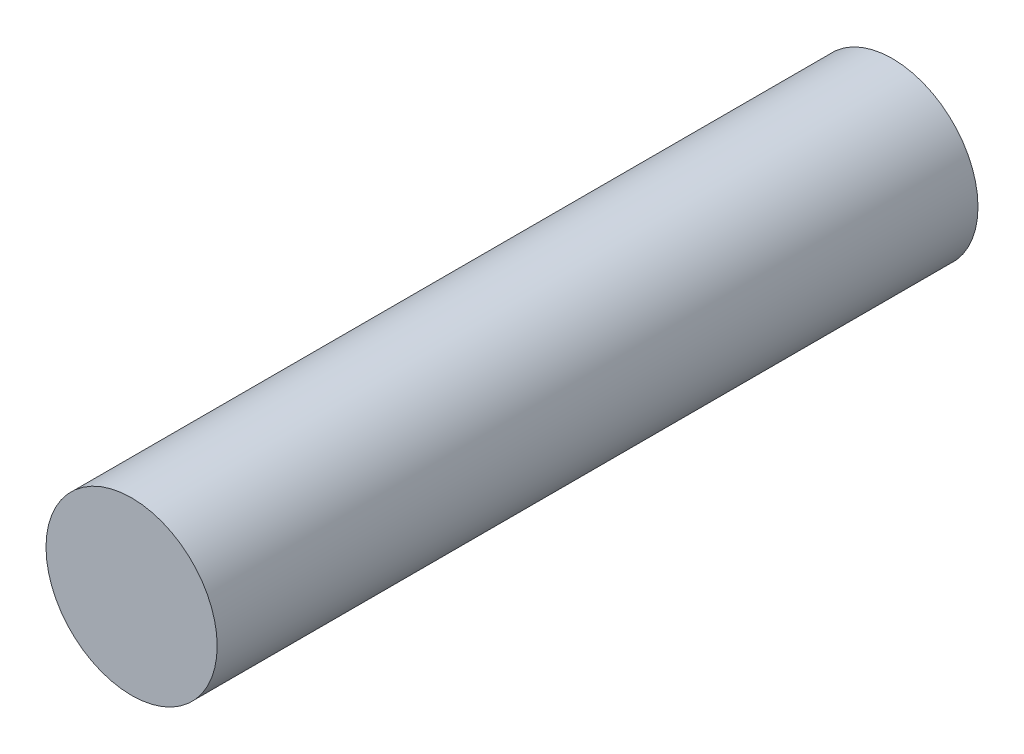
SolidWorks part; units mm, degrees
ref_plane "Спереди" through (0, 0, 0) normal (0, 0, 1) x (1, 0, 0)
ref_plane "Сверху" through (0, 0, 0) normal (0, 1, 0) x (1, 0, 0)
ref_plane "Справа" through (0, 0, 0) normal (1, 0, 0) x (0, 0, -1)
sketch "Эскиз1" plane through (0, 0, 0) normal (0, 0, 1) x (1, 0, 0)
  circle A0 centre (0, 0) radius 9
  dimension "D1" = 18
extrude "Бобышка-Вытянуть1" add sketch "Эскиз1" along normal blind 80
